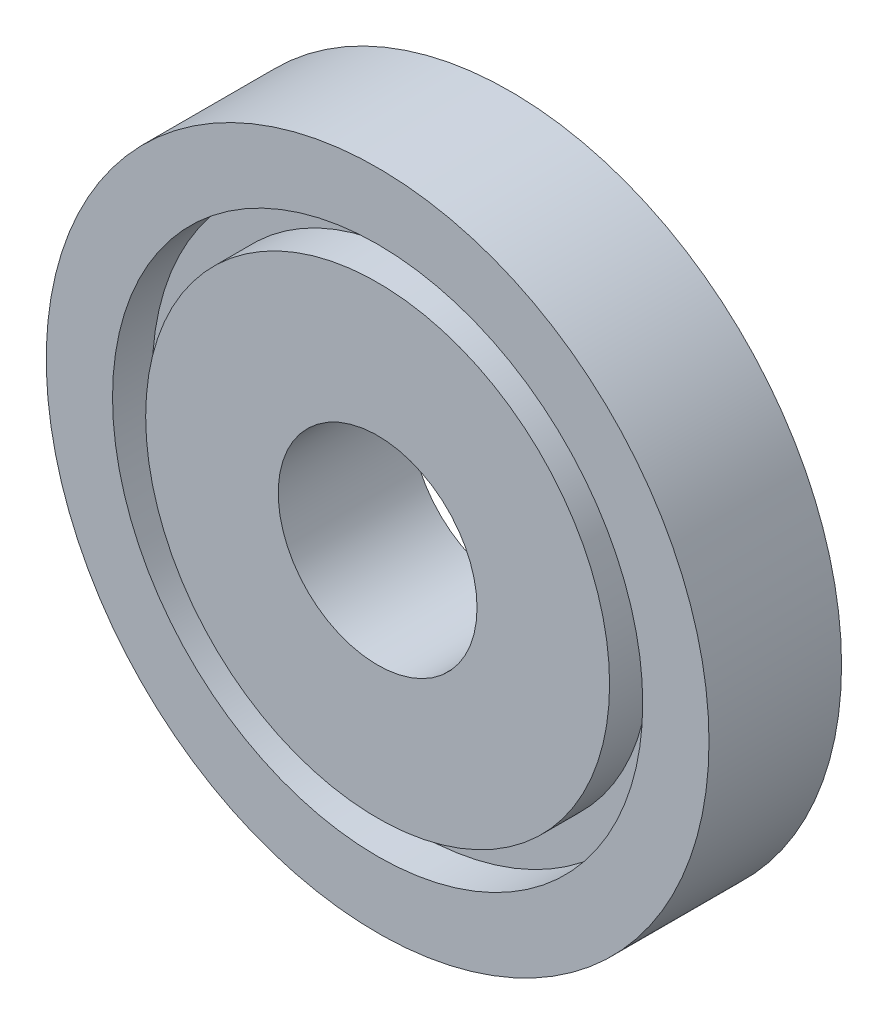
SolidWorks part; units mm, degrees
ref_plane "前视基准面" through (0, 0, 0) normal (0, 0, 1) x (1, 0, 0)
ref_plane "上视基准面" through (0, 0, 0) normal (0, 1, 0) x (1, 0, 0)
ref_plane "右视基准面" through (0, 0, 0) normal (1, 0, 0) x (0, 0, -1)
sketch "草图1" plane through (0, 0, 0) normal (0, 0, 1) x (1, 0, 0)
  circle A0 centre (0, 0) radius 50
  dimension "D1" = 100
extrude "凸台-拉伸1" add sketch "草图1" along normal mid plane 20
sketch "草图2" plane through (0, 0, 10) normal (0, 0, 1) x (1, 0, 0)
  circle A0 centre (0, 0) radius 15
  dimension "D1" = 30
extrude "切除-拉伸1" cut sketch "草图2" against normal blind 20
sketch "草图3" plane through (0, 0, 10) normal (0, 0, 1) x (1, 0, 0)
  circle A2 centre (0, 0) radius 40
  circle A3 centre (0, 0) radius 40
  circle A5 centre (0, 0) radius 35
  circle A6 centre (0, 0) radius 35
  dimension "D1" = 10
  dimension "D2" = 15
extrude "切除-拉伸3" cut sketch "草图3" against normal blind 6
mirror "镜向1" about plane through (0, 0, 0) normal (0, 0, 1) of "切除-拉伸3"
